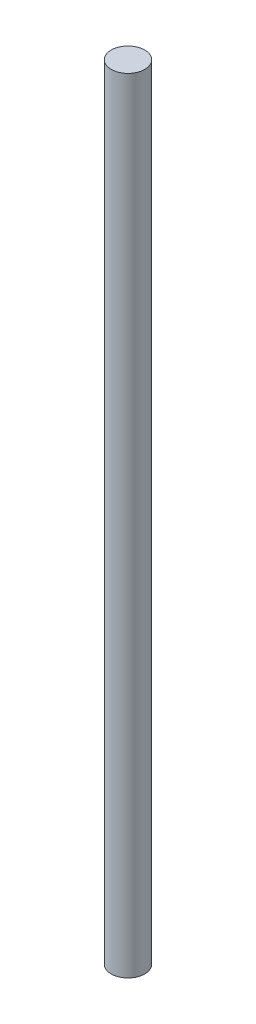
SolidWorks part; units mm, degrees
ref_plane "Front Plane" through (0, 0, 0) normal (0, 0, 1) x (1, 0, 0)
ref_plane "Top Plane" through (0, 0, 0) normal (0, 1, 0) x (1, 0, 0)
ref_plane "Right Plane" through (0, 0, 0) normal (1, 0, 0) x (0, 0, -1)
sketch "Çizim4" plane through (0, 0, 0) normal (0, 1, 0) x (1, 0, 0)
  circle A0 centre (0, 0) radius 1.5
  dimension "D1" = 3
extrude "Yükseklik-Ekstrüzyon2" add sketch "Çizim4" along normal blind 70
